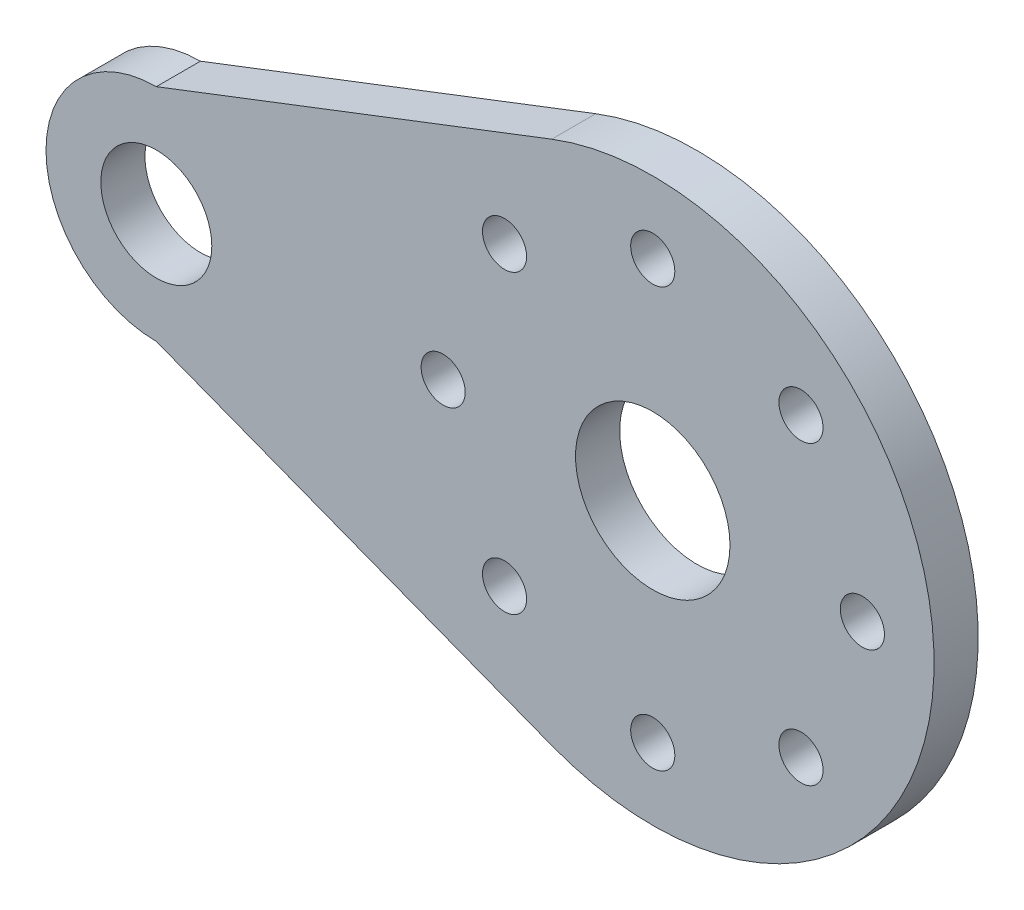
SolidWorks part; units mm, degrees
ref_plane "前视基准面" through (0, 0, 0) normal (0, 0, 1) x (1, 0, 0)
ref_plane "上视基准面" through (0, 0, 0) normal (0, 1, 0) x (1, 0, 0)
ref_plane "右视基准面" through (0, 0, 0) normal (1, 0, 0) x (0, 0, -1)
sketch "草图1" plane through (0, 0, 0) normal (0, 0, 1) x (1, 0, 0)
  line L0 (140.4648, -16.6383) -> (95.4648, -16.6383) construction
  line L1 (95.4648, -26.6383) -> (131.3031, -40.4356)
  line L2 (95.4648, -6.6383) -> (131.3031, 7.1591)
  circle A0 centre (140.4648, -16.6383) radius 7
  circle A1 centre (140.4648, -35.6383) radius 2
  circle A2 centre (127.0297, -30.0733) radius 2
  circle A3 centre (121.4648, -16.6383) radius 2
  circle A4 centre (127.0297, -3.2032) radius 2
  circle A5 centre (140.4648, -16.6383) radius 19 construction
  circle A6 centre (140.4648, 2.3617) radius 2
  circle A7 centre (153.8998, -3.2032) radius 2
  circle A8 centre (159.4648, -16.6383) radius 2
  circle A9 centre (153.8998, -30.0733) radius 2
  circle A10 centre (140.4648, -16.6383) radius 25.5 construction
  circle A11 centre (95.4648, -16.6383) radius 10 construction
  circle A12 centre (95.4648, -16.6383) radius 5.03
  arc A13 (95.4648, -26.6383) -> (95.4648, -6.6383) centre (95.4648, -16.6383) cw
  arc A14 (131.3031, 7.1591) -> (131.3031, -40.4356) centre (140.4648, -16.6383) cw
extrude "凸台-拉伸1" add sketch "草图1" along normal blind 4 contours L1 A14 L2 A13
